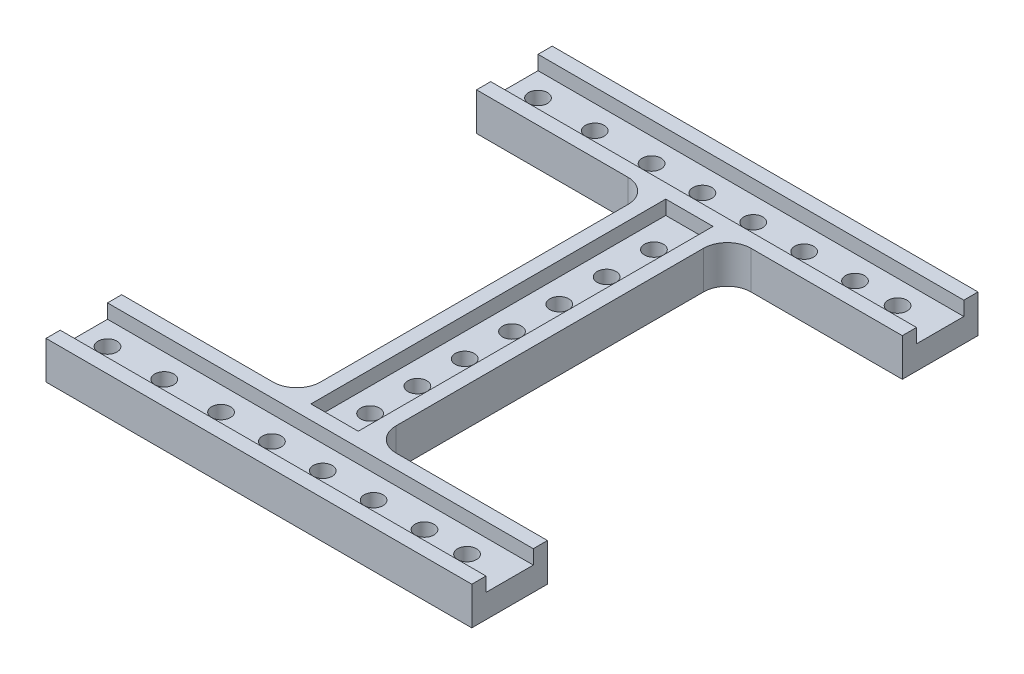
SolidWorks part; units mm, degrees
ref_plane "Front Plane" through (0, 0, 0) normal (0, 0, 1) x (1, 0, 0)
ref_plane "Top Plane" through (0, 0, 0) normal (0, 1, 0) x (1, 0, 0)
ref_plane "Right Plane" through (0, 0, 0) normal (1, 0, 0) x (0, 0, -1)
sketch "Sketch1" plane through (0, 0, 0) normal (0, 1, 0) x (1, 0, 0)
  line L1 (-51.7944, 9.8071) -> (38.2056, 9.8071)
  line L2 (-51.7944, 9.8071) -> (-51.7944, -6.1929)
  line L3 (-51.7944, -6.1929) -> (38.2056, -6.1929)
  line L4 (38.2056, 9.8071) -> (38.2056, -6.1929)
extrude "Boss-Extrude1" add sketch "Sketch1" along normal blind 5
sketch "Sketch2" plane through (0, 5, 0) normal (0, 1, 0) x (1, 0, 0)
  line L0 (-51.7944, 9.8071) -> (-51.7944, 6.8071)
  line L1 (-51.7944, 9.8071) -> (-51.7944, -6.1929) construction
  line L2 (-51.7944, 6.8071) -> (38.2056, 6.8071)
  line L3 (38.2056, -6.1929) -> (38.2056, 9.8071) construction
  line L4 (38.2056, 6.8071) -> (38.2056, 9.8071)
  line L5 (38.2056, 9.8071) -> (-51.7944, 9.8071)
  line L6 (-51.7944, -6.1929) -> (-51.7944, -3.1929)
  line L7 (-51.7944, -3.1929) -> (38.2056, -3.1929)
  line L8 (38.2056, -3.1929) -> (38.2056, -6.1929)
  line L9 (38.2056, -6.1929) -> (-51.7944, -6.1929)
extrude "Boss-Extrude2" add sketch "Sketch2" along normal blind 3
sketch "Sketch3" plane through (0, 0, 0) normal (0, -1, 0) x (1, 0, 0)
  circle A0 centre (20.2056, -1.8071) radius 2
  circle A1 centre (-22.7944, -1.8071) radius 2
extrude "Cut-Extrude2" cut sketch "Sketch3" against normal up to surface (5 mm away) up to face at (-6.7944, 5, -1.8071)
sketch "Sketch4" plane through (0, 0, 0) normal (0, -1, 0) x (1, 0, 0)
  line L0 (20.2056, -1.8071) -> (20.2056, -92.8071)
  line L1 (38.2056, -84.8071) -> (38.2056, -100.8071)
  line L2 (38.2056, -100.8071) -> (-51.7944, -100.8071)
  line L3 (-51.7944, -100.8071) -> (-51.7944, -84.8071)
  line L4 (-51.7944, -84.8071) -> (38.2056, -84.8071)
  circle A0 centre (20.2056, -92.8071) radius 2
  circle A1 centre (-22.7944, -92.8071) radius 2
extrude "Boss-Extrude3" add sketch "Sketch4" against normal blind 5 separate body
sketch "Sketch5" plane through (0, 5, 0) normal (0, 1, 0) x (1, 0, 0)
  line L0 (38.2056, 100.8071) -> (38.2056, 97.8071)
  line L1 (38.2056, 84.8071) -> (38.2056, 100.8071) construction
  line L2 (38.2056, 97.8071) -> (-51.7944, 97.8071)
  line L3 (-51.7944, 100.8071) -> (-51.7944, 84.8071) construction
  line L4 (-51.7944, 97.8071) -> (-51.7944, 100.8071)
  line L5 (-51.7944, 100.8071) -> (38.2056, 100.8071)
  line L6 (38.2056, 84.8071) -> (38.2056, 87.8071)
  line L7 (38.2056, 87.8071) -> (-51.7944, 87.8071)
  line L8 (-51.7944, 87.8071) -> (-51.7944, 84.8071)
  line L9 (-51.7944, 84.8071) -> (38.2056, 84.8071)
extrude "Boss-Extrude4" add sketch "Sketch5" along normal blind 3
sketch "Sketch6" plane through (0, 0, 0) normal (0, -1, 0) x (1, 0, 0)
  line L1 (38.2056, -9.8071) -> (-51.7944, -9.8071) construction
  line L2 (-51.7944, -84.8071) -> (38.2056, -84.8071) construction
  line L3 (-6.7944, -84.8071) -> (1.2056, -84.8071)
  line L4 (1.2056, -84.8071) -> (1.2056, -9.8071)
  line L5 (1.2056, -9.8071) -> (-14.7944, -9.8071)
  line L6 (-14.7944, -9.8071) -> (-14.7944, -84.8071)
  line L7 (-14.7944, -84.8071) -> (-6.7944, -84.8071)
extrude "Boss-Extrude5" add sketch "Sketch6" against normal blind 5 contours L3 L4 L5 L6 L7
sketch "Sketch7" plane through (0, 5, 0) normal (0, 1, 0) x (1, 0, 0)
  line L0 (1.2056, 84.8071) -> (-1.7944, 84.8071)
  line L1 (-14.7944, 84.8071) -> (1.2056, 84.8071) construction
  line L2 (-1.7944, 84.8071) -> (-1.7944, 9.8071)
  line L3 (1.2056, 9.8071) -> (-14.7944, 9.8071) construction
  line L4 (-1.7944, 9.8071) -> (1.2056, 9.8071)
  line L5 (1.2056, 9.8071) -> (1.2056, 84.8071)
  line L6 (-14.7944, 9.8071) -> (-11.7944, 9.8071)
  line L7 (-11.7944, 9.8071) -> (-11.7944, 84.8071)
  line L8 (-11.7944, 84.8071) -> (-14.7944, 84.8071)
  line L10 (-14.7944, 84.8071) -> (-14.7944, 9.8071)
extrude "Boss-Extrude6" add sketch "Sketch7" along normal blind 3
sketch "Sketch8" plane through (0, 5, 0) normal (0, 1, 0) x (1, 0, 0)
  circle A0 centre (-46.7944, 92.8071) radius 2
  circle A2 centre (-34.7944, 92.8071) radius 2
  circle A3 centre (29.2056, 92.8071) radius 2
  circle A4 centre (9.4556, 92.8071) radius 2
  circle A5 centre (-1.2944, 92.8071) radius 2
  circle A7 centre (-12.0444, 92.8071) radius 2
  circle A8 centre (-1.2944, 1.8071) radius 2
  circle A9 centre (-12.0444, 1.8071) radius 2
  circle A10 centre (9.4556, 1.8071) radius 2
  circle A11 centre (-34.7944, 1.8071) radius 2
  circle A12 centre (29.2056, 1.8071) radius 2
  circle A13 centre (-46.7944, 1.8071) radius 2
extrude "Cut-Extrude5" cut sketch "Sketch8" against normal up to surface (5 mm away) up to face at (20.2056, 0, -3.8071)
sketch "Sketch9" plane through (0, 5, 0) normal (0, 1, 0) x (1, 0, 0)
  circle A0 centre (-6.7944, 47.3071) radius 2
  circle A1 centre (-6.7944, 57.3071) radius 2
  circle A2 centre (-6.7944, 67.3071) radius 2
  circle A3 centre (-6.7944, 77.3071) radius 2
  circle A4 centre (-6.7944, 37.3071) radius 2
  circle A5 centre (-6.7944, 27.3071) radius 2
  circle A6 centre (-6.7944, 17.3071) radius 2
  dimension "D1" = 4
  dimension "D2" = 4
extrude "Cut-Extrude6" cut sketch "Sketch9" against normal up to surface (5 mm away) up to face at (-34.7944, 0, 0.1929)
fillet "Fillet1" radius 5 4 edges at (-14.7944, 4, -9.8071) (-14.7944, 4, -84.8071) (1.2056, 4, -84.8071) (1.2056, 4, -9.8071)
sketch "Sketch10" plane through (0, 0, 0) normal (0, -1, 0) x (1, 0, 0)
  circle A0 centre (20.2056, -1.8071) radius 4
  circle A1 centre (-22.7944, -1.8071) radius 4
  circle A2 centre (20.2056, -92.8071) radius 4
  circle A3 centre (-22.7944, -92.8071) radius 4
extrude "Cut-Extrude7" cut sketch "Sketch10" against normal blind 2
sketch "Sketch11" plane through (0, 0, 0) normal (0, -1, 0) x (1, 0, 0)
  circle A0 centre (-46.7944, -1.8071) radius 4
  circle A1 centre (-46.7944, -92.8071) radius 4
extrude "Cut-Extrude8" cut sketch "Sketch11" against normal blind 2
